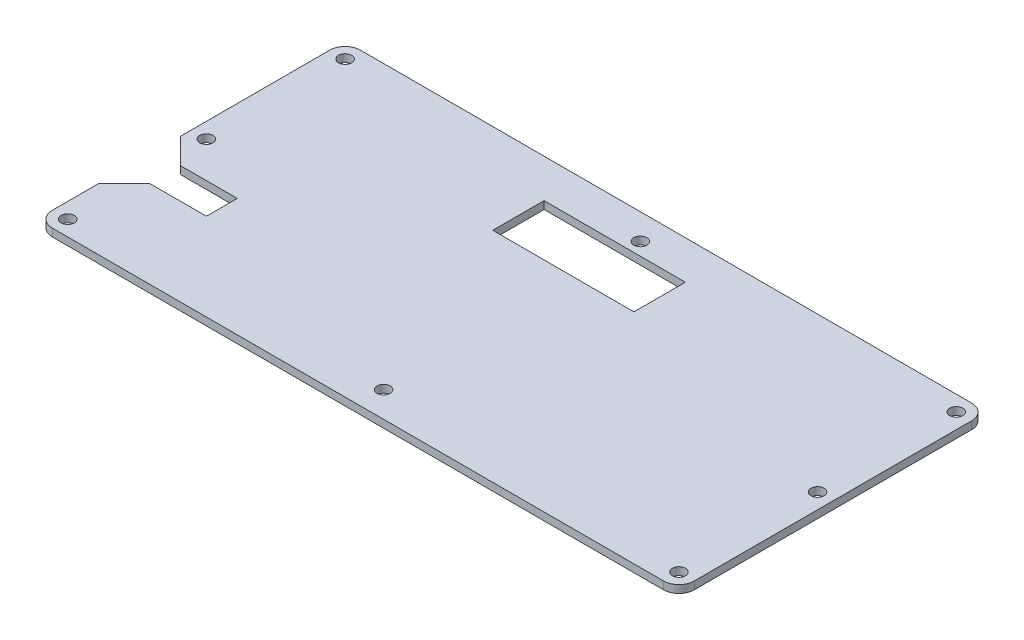
SolidWorks part; units mm, degrees
ref_plane "前视基准面" through (0, 0, 0) normal (0, 0, 1) x (1, 0, 0)
ref_plane "上视基准面" through (0, 0, 0) normal (0, 1, 0) x (1, 0, 0)
ref_plane "右视基准面" through (0, 0, 0) normal (1, 0, 0) x (0, 0, -1)
sketch "草图1" plane through (0, 0, 0) normal (0, 1, 0) x (1, 0, 0)
  line L0 (16.2077, 68.2336) -> (16.2077, 126.2336)
  line L1 (22.2077, 132.2336) -> (260.2077, 132.2336)
  line L2 (266.2077, 126.2336) -> (266.2077, 18.2336)
  line L3 (260.2077, 12.2336) -> (22.2077, 12.2336)
  line L4 (16.2077, 18.2336) -> (16.2077, 36.2336)
  line L5 (26.2077, 58.2336) -> (16.2077, 68.2336)
  line L6 (26.2077, 46.2336) -> (16.2077, 36.2336)
  line L7 (108.7077, 97.2336) -> (108.7077, 117.2336)
  line L8 (163.7077, 117.2336) -> (163.7077, 97.2336)
  line L9 (108.7077, 117.2336) -> (163.7077, 117.2336)
  line L10 (163.7077, 97.2336) -> (108.7077, 97.2336)
  line L11 (26.2077, 58.2336) -> (48.2077, 58.2336)
  line L12 (48.2077, 58.2336) -> (48.2077, 46.2336)
  line L13 (48.2077, 46.2336) -> (26.2077, 46.2336)
  arc A0 (22.2077, 132.2336) -> (16.2077, 126.2336) centre (22.2077, 126.2336) ccw
  arc A1 (266.2077, 126.2336) -> (260.2077, 132.2336) centre (260.2077, 126.2336) ccw
  arc A2 (260.2077, 12.2336) -> (266.2077, 18.2336) centre (260.2077, 18.2336) ccw
  arc A3 (16.2077, 18.2336) -> (22.2077, 12.2336) centre (22.2077, 18.2336) ccw
  circle A4 centre (22.2077, 126.2336) radius 2.55
  circle A5 centre (260.2077, 126.2336) radius 2.55
  circle A6 centre (141.2077, 122.2336) radius 2.55
  circle A7 centre (22.2077, 18.2336) radius 2.55
  circle A8 centre (260.2077, 18.2336) radius 2.55
  circle A9 centre (141.2077, 22.2336) radius 2.55
  circle A10 centre (260.2077, 72.2336) radius 2.55
  circle A11 centre (22.2077, 72.2336) radius 2.55
extrude "凸台-拉伸1" add sketch "草图1" along normal blind 3
